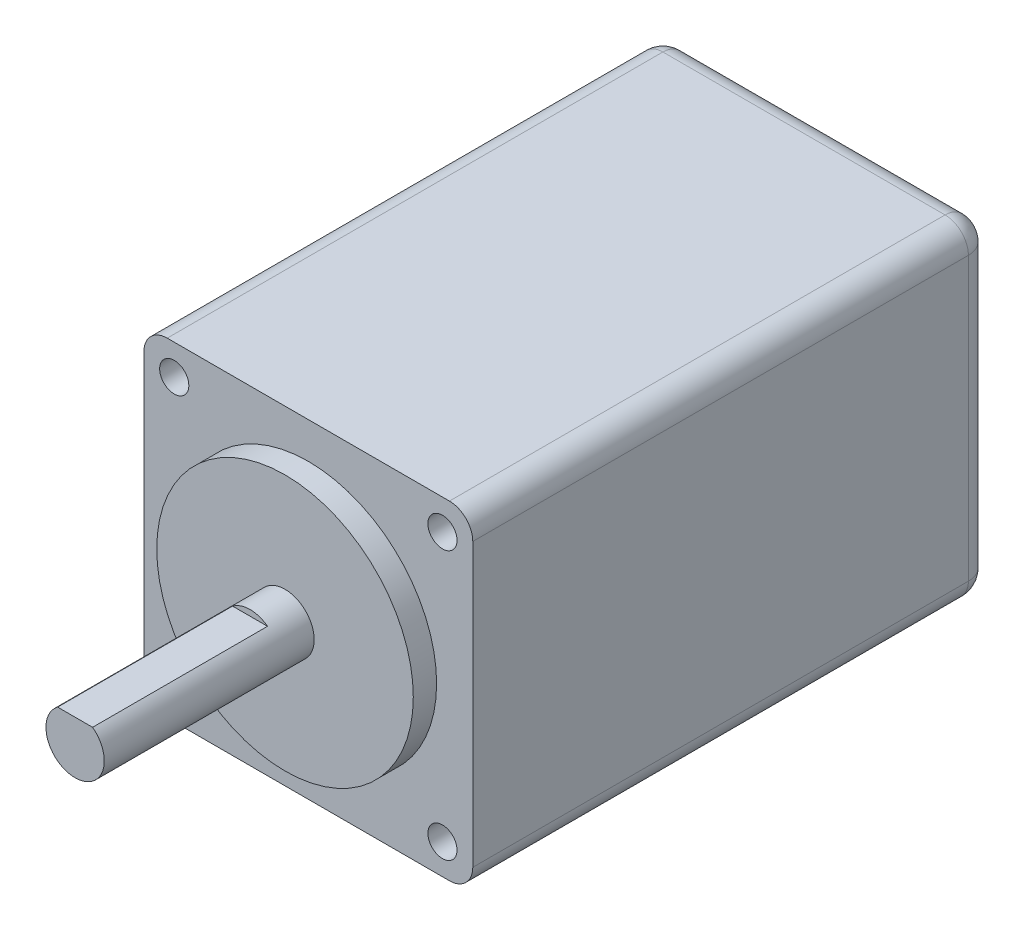
SolidWorks part; units mm, degrees
ref_plane "Front Plane" through (0, 0, 0) normal (0, 0, 1) x (1, 0, 0)
ref_plane "Top Plane" through (0, 0, 0) normal (0, 1, 0) x (1, 0, 0)
ref_plane "Right Plane" through (0, 0, 0) normal (1, 0, 0) x (0, 0, -1)
sketch "Sketch1" plane through (0, 0, 0) normal (0, 0, 1) x (1, 0, 0)
  line L1 (-14.1, -14.1) -> (14.1, -14.1)
  line L2 (-14.1, -14.1) -> (-14.1, 14.1)
  line L3 (-14.1, 14.1) -> (14.1, 14.1)
  line L4 (14.1, -14.1) -> (14.1, 14.1)
  line L5 (-14.1, -14.1) -> (14.1, 14.1) construction
  line L6 (-14.1, 14.1) -> (14.1, -14.1) construction
  point P0 (0, 0)
  dimension "D1" = 28.2
  dimension "D2" = 28.2
extrude "Boss-Extrude1" add sketch "Sketch1" along normal blind 44.5
sketch "Sketch2" plane through (0, 0, 44.5) normal (0, 0, 1) x (1, 0, 0)
  circle A0 centre (0, 0) radius 11
  dimension "D1" = 22
extrude "Boss-Extrude2" add sketch "Sketch2" along normal blind 2
sketch "Sketch3" plane through (0, 0, 46.5) normal (0, 0, 1) x (1, 0, 0)
  circle A0 centre (0, 0) radius 2.5
  dimension "D1" = 5
extrude "Boss-Extrude3" add sketch "Sketch3" along normal blind 18
sketch "Sketch4" plane through (0, 0, 0) normal (1, 0, 0) x (0, 0, -1)
  line L1 (-64.5, 2.5) -> (-49.5, 2.5)
  line L2 (-64.5, 2.5) -> (-64.5, 2)
  line L3 (-64.5, 2) -> (-49.5, 2)
  line L4 (-49.5, 2.5) -> (-49.5, 2)
  dimension "D1" = 15
  dimension "D2" = 0.5
extrude "Cut-Extrude1" cut sketch "Sketch4" against normal mid plane 10
sketch "Sketch5" plane through (0, 0, 44.5) normal (0, 0, 1) x (1, 0, 0)
  line L1 (-11.5, -11.5) -> (11.5, -11.5) construction
  line L2 (-11.5, -11.5) -> (-11.5, 11.5) construction
  line L3 (-11.5, 11.5) -> (11.5, 11.5) construction
  line L4 (11.5, -11.5) -> (11.5, 11.5) construction
  line L5 (-11.5, -11.5) -> (11.5, 11.5) construction
  line L6 (-11.5, 11.5) -> (11.5, -11.5) construction
  circle A0 centre (-11.5, 11.5) radius 1.25
  circle A1 centre (11.5, 11.5) radius 1.25
  circle A2 centre (11.5, -11.5) radius 1.25
  circle A3 centre (-11.5, -11.5) radius 1.25
  point P0 (0, 0)
  dimension "D3" = 2.5
  dimension "D1" = 23
  dimension "D2" = 23
  dimension "D4" = 4
extrude "Cut-Extrude2" cut sketch "Sketch5" against normal blind 2.5
fillet "Fillet1" radius 2 8 edges at (0, 14.1, 0) (-14.1, 0, 0) (0, -14.1, 0) (14.1, 0, 0) (-14.1, -14.1, 22.25) (14.1, -14.1, 22.25) (-14.1, 14.1, 22.25) (14.1, 14.1, 22.25)
